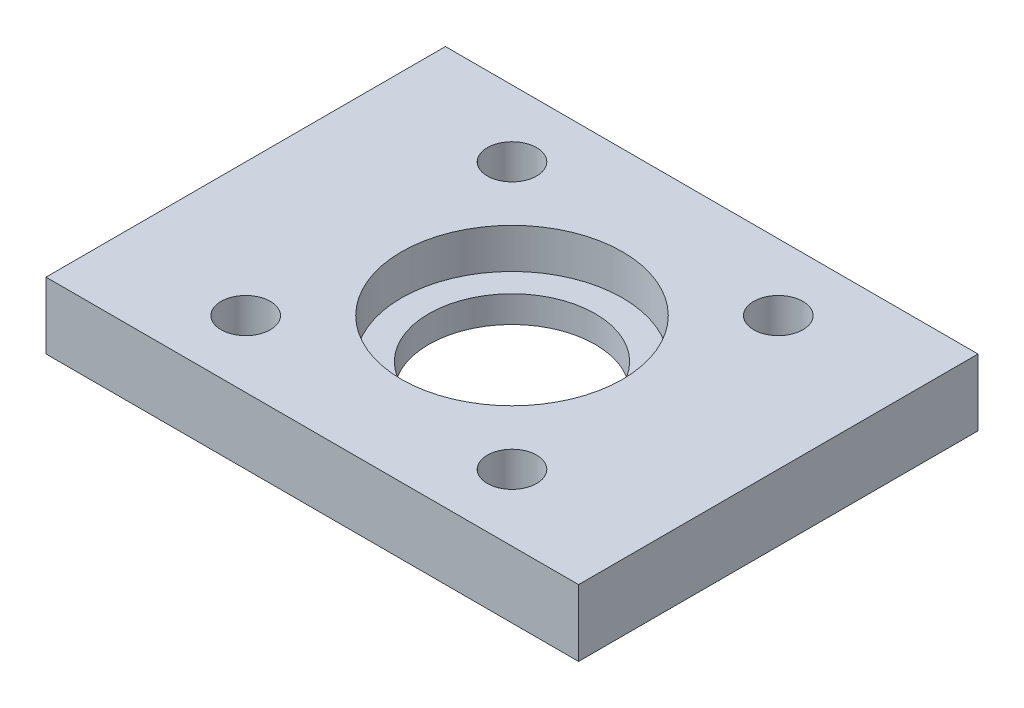
SolidWorks part; units mm, degrees
ref_plane "Front Plane" through (0, 0, 0) normal (0, 0, 1) x (1, 0, 0)
ref_plane "Top Plane" through (0, 0, 0) normal (0, 1, 0) x (1, 0, 0)
ref_plane "Right Plane" through (0, 0, 0) normal (1, 0, 0) x (0, 0, -1)
sketch "Sketch1" plane through (0, 0, 0) normal (0, 1, 0) x (1, 0, 0)
  line L1 (20, -15) -> (-20, -15)
  line L2 (20, -15) -> (20, 15)
  line L3 (20, 15) -> (-20, 15)
  line L4 (-20, -15) -> (-20, 15)
  line L5 (20, -15) -> (-20, 15) construction
  line L6 (20, 15) -> (-20, -15) construction
  circle A0 centre (0, 0) radius 6.25
  point P0 (0, 0)
  dimension "D3" = 12.5
  dimension "D1" = 40
  dimension "D2" = 30
extrude "Body" add sketch "Sketch1" along normal blind 2
sketch "Sketch2" plane through (0, 2, 0) normal (0, 1, 0) x (1, 0, 0)
  line L4 (-20, 15) -> (-20, -15)
  line L5 (-20, -15) -> (20, -15)
  line L6 (20, -15) -> (20, 15)
  line L7 (20, 15) -> (-20, 15)
  line L8 (-20, 15) -> (-20, -15)
  line L9 (-20, -15) -> (20, -15)
  line L10 (20, -15) -> (20, 15)
  line L11 (20, 15) -> (-20, 15)
  circle A4 centre (0, 0) radius 8.3
  point P2 (0, 0)
  dimension "D5" = 16.6
  dimension "D1" = 0
extrude "Bearings_Place" add sketch "Sketch2" along normal blind 3
sketch "Sketch3" plane through (0, 5, 0) normal (0, 1, 0) x (1, 0, 0)
  line L1 (10, -10) -> (-10, -10) construction
  line L2 (10, -10) -> (10, 10) construction
  line L3 (10, 10) -> (-10, 10) construction
  line L4 (-10, -10) -> (-10, 10) construction
  line L5 (10, -10) -> (-10, 10) construction
  line L6 (10, 10) -> (-10, -10) construction
  circle A0 centre (-10, 10) radius 1.85
  circle A1 centre (10, 10) radius 1.85
  circle A2 centre (10, -10) radius 1.85
  circle A3 centre (-10, -10) radius 1.85
  point P0 (0, 0)
  dimension "D1" = 3.7
  dimension "D2" = 20
extrude "Inserts_Place" cut sketch "Sketch3" against normal blind 4
